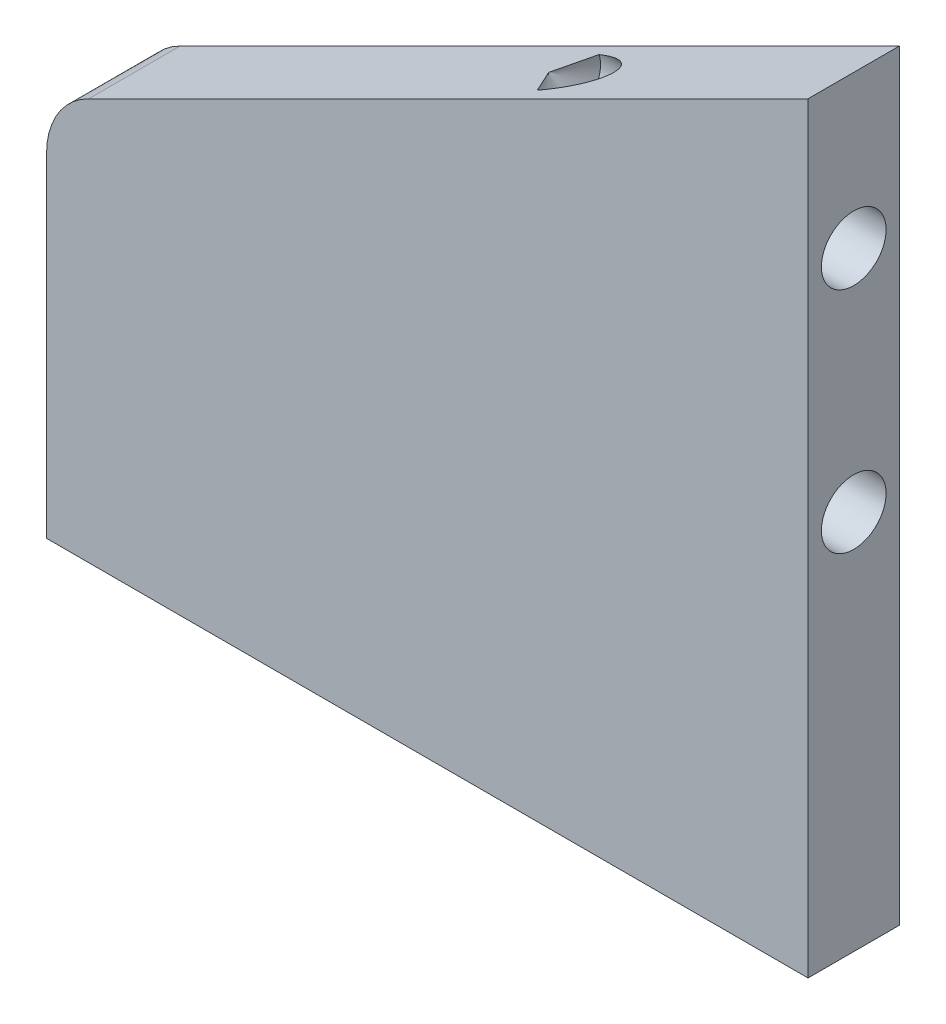
SolidWorks part; units mm, degrees
ref_plane "Vorne" through (0, 0, 0) normal (0, 0, 1) x (1, 0, 0)
ref_plane "Oben" through (0, 0, 0) normal (0, 1, 0) x (1, 0, 0)
ref_plane "Rechts" through (0, 0, 0) normal (1, 0, 0) x (0, 0, -1)
ref_plane "E_Boden" through (0, 1, 0) normal (0, 1, 0) x (1, 0, 0)
sketch "Skizze1" plane through (0, 0, 0) normal (0, 0, 1) x (1, 0, 0)
  line L0 (0, 10) -> (0, -9.5229) construction
  line L1 (-15.5467, 0) -> (14.4334, 0) construction
  line L2 (100, 0) -> (100, 100)
  line L4 (0, 0) -> (100, 0)
  line L5 (0, 0) -> (0, 50)
  line L6 (0, 50) -> (100, 100)
  dimension "D1" = 100
  dimension "D2" = 100
  dimension "D3" = 50
extrude "Aufsatz-Linear austragen1" add sketch "Skizze1" along normal blind 12
hole_wizard "M10 Gewindebohrung1" positions "Skizze2" profile "Skizze3" tap size "M10" standard "DIN"
sketch "Skizze2" plane through (0, 0, 0) normal (0, -1, 0) x (-1, 0, 0)
  line L0 (0, -6) -> (-100, -6) construction
  line L1 (0, -12) -> (0, 0) construction
  line L2 (-100, -12) -> (-100, 0) construction
  line L4 (-50, 0) -> (-50, -12) construction
  line L5 (0, 0) -> (-100, 0) construction
  line L6 (0, -12) -> (-100, -12) construction
  point P0 (-15, -6)
  point P2 (-85, -6)
  dimension "D1" = 70
  dimension "D2" = 35
cosmetic thread "Bohrungsgewinde1" parameters "D1"=30, "D2"=10
cosmetic thread "Bohrungsgewinde2" parameters "D1"=30, "D2"=10
sketch "Skizze3" plane through (15, 0, 6) normal (1, 0, 0) x (0, 0, -1)
  line L0 (0, 0) -> (0, 40.0537)
  line L1 (0, 40.0537) -> (4.25, 37.5)
  line L2 (4.25, 37.5) -> (4.25, 0)
  line L5 (4.25, 0) -> (0, 0)
  line L10 (0, 40.0537) -> (-4.25, 37.5) construction
  line L11 (0, -6.35) -> (0, 107.95) construction
  dimension "Bohrerdurchmesser" = 8.5
  dimension "Bohrungstiefe" = 37.5
  dimension "Spitzenwinkel" = 118
hole_wizard "M10 Gewindebohrung2" positions "Skizze4" profile "Skizze5" tap size "M10" standard "DIN"
sketch "Skizze4" plane through (100, 0, 0) normal (1, 0, 0) x (0, 0, -1)
  line L0 (-6, 0) -> (-6, 100) construction
  line L1 (-12, 0) -> (0, 0) construction
  line L2 (-12, 100) -> (0, 100) construction
  point P0 (-6, 50)
  point P2 (-6, 80)
  point P12 (-6, 50)
  point P13 (-6, 50)
  point P14 (-5.0018, 85)
  point P15 (-6, 76.103)
  point P16 (0, 0)
  point P17 (-6, 46.0583)
  point P18 (-6, 49.5259)
  point P19 (-6, 46.3988)
  point P20 (0, 0)
  point P21 (-6, 80.8049)
  point P22 (0, 0)
  point P23 (0, 0)
  dimension "D1" = 20
  dimension "D2" = 30
sketch "Skizze5" plane through (100, 50, 6) normal (0, 1, 0) x (0, 0, -1)
  line L0 (0, 0) -> (0, 40.0537)
  line L1 (0, 40.0537) -> (4.25, 37.5)
  line L2 (4.25, 37.5) -> (4.25, 0)
  line L5 (4.25, 0) -> (0, 0)
  line L10 (0, 40.0537) -> (-4.25, 37.5) construction
  line L11 (0, -6.35) -> (0, 107.95) construction
  dimension "Bohrerdurchmesser" = 8.5
  dimension "Bohrungstiefe" = 37.5
  dimension "Spitzenwinkel" = 118
cosmetic thread "Bohrungsgewinde3" parameters "D1"=30, "D2"=10
cosmetic thread "Bohrungsgewinde4" parameters "D1"=30, "D2"=10
fillet "Verrundung1" radius 10 1 edges at (0, 50, 6)
